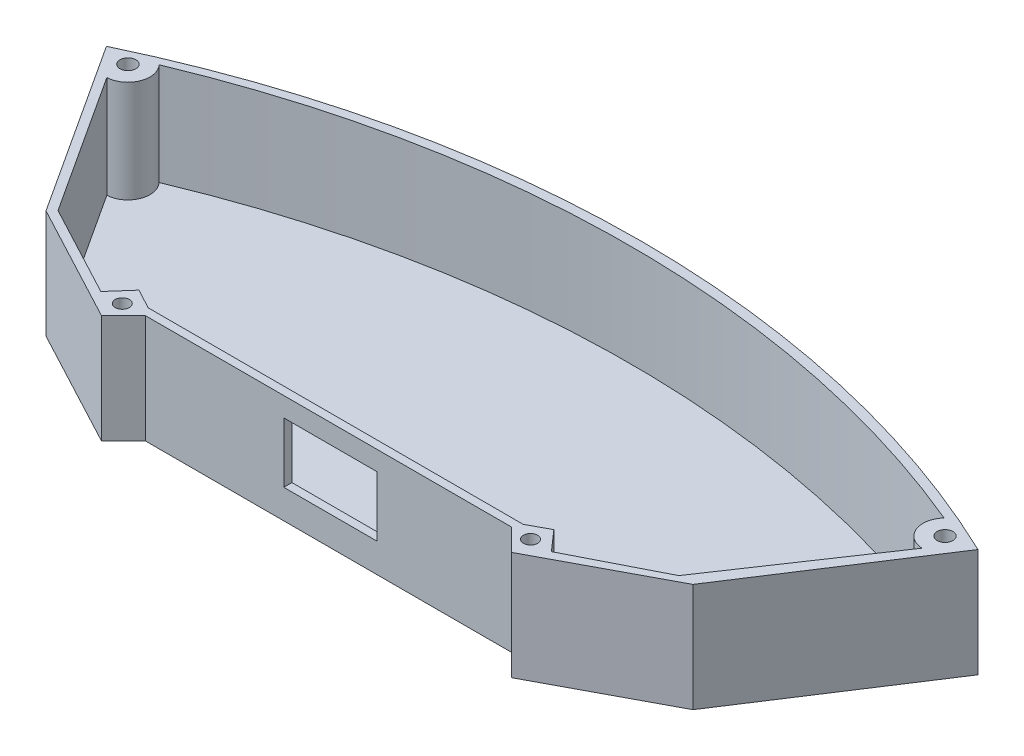
SolidWorks part; units mm, degrees
ref_plane "Front Plane" through (0, 0, 0) normal (0, 0, 1) x (1, 0, 0)
ref_plane "Top Plane" through (0, 0, 0) normal (0, 1, 0) x (1, 0, 0)
ref_plane "Right Plane" through (0, 0, 0) normal (1, 0, 0) x (0, 0, -1)
sketch "Sketch1" plane through (0, 0, 0) normal (0, 1, 0) x (1, 0, 0)
  line L1 (-46.023, 40.2701) -> (49.277, 40.2701)
  line L2 (-46.023, 40.2701) -> (-46.023, -38.7299)
  line L3 (-46.023, -38.7299) -> (49.277, -38.7299)
  line L4 (49.277, 40.2701) -> (49.277, -38.7299)
  dimension "D1" = 79
  dimension "D2" = 95.3
extrude "Boss-Extrude1" add sketch "Sketch1" along normal blind 33
sketch "Sketch3" plane through (0, 0, 0) normal (0, 1, 0) x (1, 0, 0)
  line L0 (49.277, 40.2701) -> (-46.023, 40.2701) construction
  line L1 (-44.023, 38.2701) -> (47.277, 38.2701)
  line L2 (-44.023, 38.2701) -> (-44.023, -36.7299)
  line L3 (-44.023, -36.7299) -> (47.277, -36.7299)
  line L4 (47.277, 38.2701) -> (47.277, -36.7299)
  line L5 (-46.023, 40.2701) -> (-46.023, -38.7299) construction
  line L6 (49.277, -38.7299) -> (49.277, 40.2701) construction
  line L7 (-46.023, -38.7299) -> (49.277, -38.7299) construction
  point P4 (1.627, 38.2701)
  point P7 (-44.023, 0.7701)
  dimension "D1" = 2
  dimension "D2" = 2
  dimension "D3" = 2
  dimension "D4" = 2
sketch "Sketch4" plane through (0, 0, 0) normal (0, 0, 1) x (1, 0, 0)
  line L1 (-38.5534, 22.5822) -> (-18.7534, 22.5822)
  line L2 (-38.5534, 22.5822) -> (-38.5534, 10.8822)
  line L3 (-38.5534, 10.8822) -> (-18.7534, 10.8822)
  line L4 (-18.7534, 22.5822) -> (-18.7534, 10.8822)
  dimension "D1" = 19.8
  dimension "D2" = 11.7
sketch "Sketch5" plane through (0, 0, 0) normal (1, 0, 0) x (0, 0, -1)
  line L1 (12.8382, 22.2927) -> (29.2509, 22.2927)
  line L2 (12.8382, 22.2927) -> (12.8382, 10.8682)
  line L3 (12.8382, 10.8682) -> (29.2509, 10.8682)
  line L4 (29.2509, 22.2927) -> (29.2509, 10.8682)
extrude "Cut-Extrude3" cut sketch "Sketch5" along normal blind 51
extrude "Cut-Extrude4" cut sketch "Sketch4" along normal blind 51
sketch "Sketch6" plane through (0, 0, 0) normal (0, 1, 0) x (1, 0, 0)
  line L3 (-54.023, -46.7299) -> (57.277, -46.7299)
  line L7 (-46.023, -38.7299) -> (49.277, -38.7299) construction
  line L11 (-54.023, 43.1943) -> (-54.023, -46.7299)
  line L13 (57.277, 43.1943) -> (57.277, -46.7299)
  arc A1 (-54.023, 43.1943) -> (57.277, 43.1943) centre (1.627, -259.3341) cw
  point P12 (1.627, -46.7299)
  point P19 (1.627, 18.2701)
  dimension "D4" = 8
extrude "Boss-Extrude2" add sketch "Sketch6" along normal blind 3 from offset 30
sketch "Sketch7" plane through (0, 0, 0) normal (0, 1, 0) x (1, 0, 0)
  line L4 (-54.023, -46.7299) -> (-60.7009, -53.4078)
  line L6 (-60.7009, -53.4078) -> (-96.724, -34.2531)
  line L7 (-96.724, -34.2531) -> (-130.873, 18.2701)
  line L8 (99.978, -34.2531) -> (134.127, 18.2701)
  line L14 (63.955, -53.4078) -> (99.978, -34.2531)
  line L15 (57.277, -46.7299) -> (63.955, -53.4078)
  line L16 (-54.023, -46.7299) -> (57.277, -46.7299)
  arc A2 (-130.873, 18.2701) -> (134.127, 18.2701) centre (1.627, -259.3341) cw
extrude "Cut-Extrude6" cut sketch "Sketch3" along normal blind 33 from offset 2
extrude "Boss-Extrude3" add sketch "Sketch7" along normal blind 33
sketch "Sketch12" plane through (0, 0, 0) normal (0, 1, 0) x (1, 0, 0)
  line L7 (-55.6752, -44.2479) -> (-61.7177, -40.9811)
  line L8 (-61.7177, -40.9811) -> (-67.1479, -47.1483)
  line L9 (69.84, -47.1483) -> (95.5187, -34.0903)
  line L11 (58.3673, -44.2479) -> (-55.6752, -44.2479)
  line L18 (58.3673, -44.2479) -> (64.4097, -40.9811)
  line L19 (64.4097, -40.9811) -> (69.84, -47.1483)
  line L20 (95.5187, -34.0903) -> (125.275, 10.1059)
  line L21 (-94.9801, -32.349) -> (-67.1479, -47.1483)
  line L22 (-122.5829, 10.1059) -> (-94.9801, -32.349)
  arc A1 (-118.0091, 21.4108) -> (-122.5829, 10.1059) centre (-122.8819, 16.8045) cw
  arc A2 (120.7012, 21.4108) -> (125.275, 10.1059) centre (125.5739, 16.8045) ccw
  arc A3 (-118.0091, 21.4108) -> (120.7012, 21.4108) centre (1.346, -264.1839) cw
extrude "Cut-Extrude7" cut sketch "Sketch12" along normal blind 33 from offset 2
sketch "Sketch13" plane through (0, 0, 0) normal (0, 0, 1) x (1, 0, 0)
  line L1 (-11.9525, 27.1186) -> (16.3248, 27.1186)
  line L2 (-11.9525, 27.1186) -> (-11.9525, 8.834)
  line L3 (-11.9525, 8.834) -> (16.3248, 8.834)
  line L4 (16.3248, 27.1186) -> (16.3248, 8.834)
extrude "Cut-Extrude8" cut sketch "Sketch13" along normal blind 63
sketch "Sketch15" plane through (0, 0, 0) normal (0, 1, 0) x (1, 0, 0)
  circle A0 centre (-122.8819, 16.8045) radius 2.4045
  arc A1 (-122.5829, 10.1059) -> (-118.0091, 21.4108) centre (-122.8819, 16.8045) ccw construction
  circle A2 centre (-60.7281, -47.0586) radius 2.15
  circle A3 centre (63.4202, -47.0586) radius 2.15
  circle A4 centre (125.5739, 16.8045) radius 2.4045
  dimension "D1" = 4.3007
  dimension "D2" = 4.3
extrude "Cut-Extrude9" cut sketch "Sketch15" along normal blind 63 from offset 15
